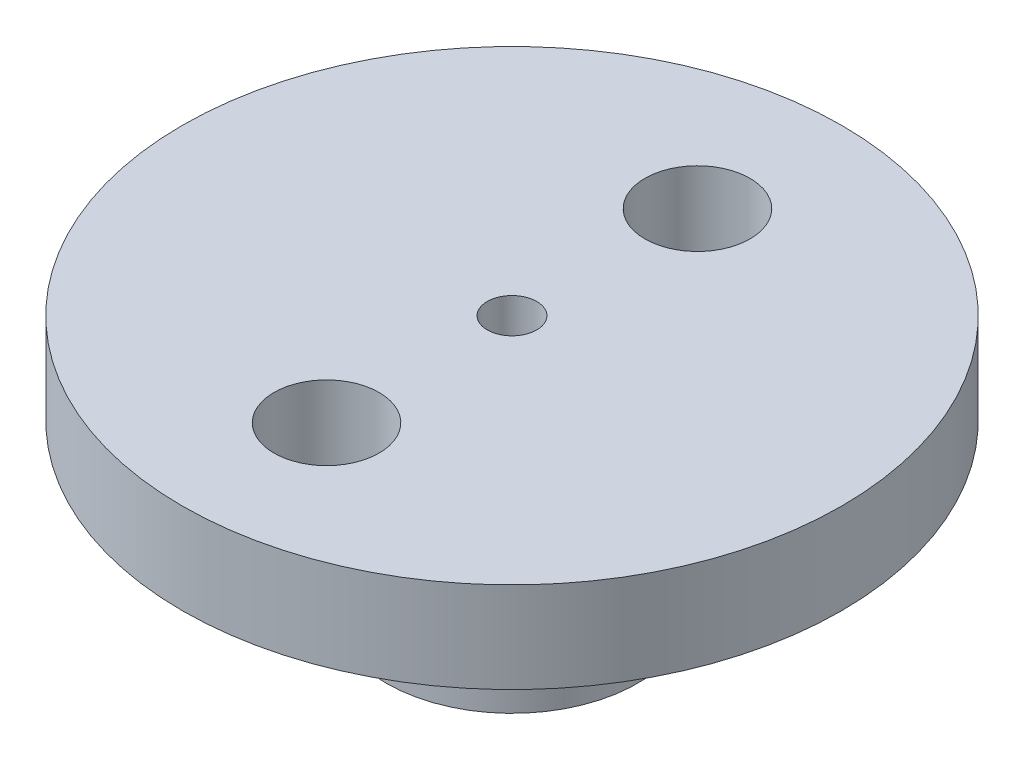
SolidWorks part; units mm, degrees
ref_plane "Front Plane" through (0, 0, 0) normal (0, 0, 1) x (1, 0, 0)
ref_plane "Top Plane" through (0, 0, 0) normal (0, 1, 0) x (1, 0, 0)
ref_plane "Right Plane" through (0, 0, 0) normal (1, 0, 0) x (0, 0, -1)
sketch "Sketch1" plane through (0, 0, 0) normal (0, 1, 0) x (1, 0, 0)
  circle A0 centre (0, 0) radius 8
  dimension "D1" = 16
extrude "Boss-Extrude1" add sketch "Sketch1" along normal blind 2.2
sketch "Sketch2" plane through (0, 2.2, 0) normal (0, 1, 0) x (1, 0, 0)
  line L0 (0, -16.0698) -> (0, 16.0698) construction
  line L1 (-27.9531, 0) -> (27.9531, 0) construction
  circle A2 centre (0, 4.5) radius 1.275
  circle A12 centre (0, -4.5) radius 1.275
  point P3 (0, 0)
  point P9 (0, 0)
  dimension "D1" = 2.55
  dimension "D2" = 4.5
extrude "Cut-Extrude1" cut sketch "Sketch2" against normal blind 2.2
sketch "Sketch3" plane through (0, 0, 0) normal (0, -1, 0) x (1, 0, 0)
  circle A0 centre (0, 0) radius 3.05
  circle A1 centre (0, 0) radius 2.3
  dimension "D1" = 6.1
  dimension "D2" = 4.6
extrude "Boss-Extrude2" add sketch "Sketch3" along normal blind 4
sketch "Sketch8" plane through (0, 0, 0) normal (0, -1, 0) x (1, 0, 0)
  circle A0 centre (0, 0) radius 0.6
  dimension "D1" = 1.2
extrude "Cut-Extrude7" cut sketch "Sketch8" against normal up to surface (2.2 mm away) up to face at (0, 2.2, 3.225)
sketch "Sketch9" plane through (0, -4, 0) normal (0, -1, 0) x (-1, 0, 0)
